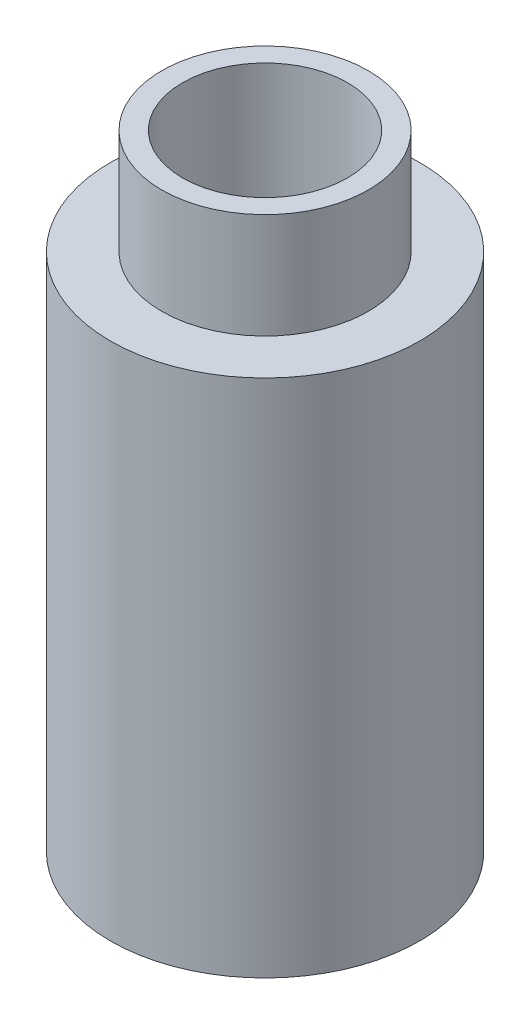
SolidWorks part; units mm, degrees
ref_plane "Front Plane" through (0, 0, 0) normal (0, 0, 1) x (1, 0, 0)
ref_plane "Top Plane" through (0, 0, 0) normal (0, 1, 0) x (1, 0, 0)
ref_plane "Right Plane" through (0, 0, 0) normal (1, 0, 0) x (0, 0, -1)
sketch "Sketch1" plane through (0, 0, 0) normal (0, 1, 0) x (1, 0, 0)
  circle A0 centre (0, 0) radius 9.4488
  dimension "D1" = 18.8976
extrude "Boss-Extrude1" add sketch "Sketch1" along normal blind 31.75
sketch "Sketch2" plane through (0, 31.75, 0) normal (0, 1, 0) x (1, 0, 0)
  circle A0 centre (0, 0) radius 6.3119
  dimension "D1" = 12.6238
extrude "Boss-Extrude2" add sketch "Sketch2" along normal blind 6.4262
sketch "Sketch3" plane through (0, 38.1762, 0) normal (0, 1, 0) x (1, 0, 0)
  circle A0 centre (0, 0) radius 5.0419
  dimension "D1" = 10.0838
extrude "Cut-Extrude1" cut sketch "Sketch3" against normal through all
